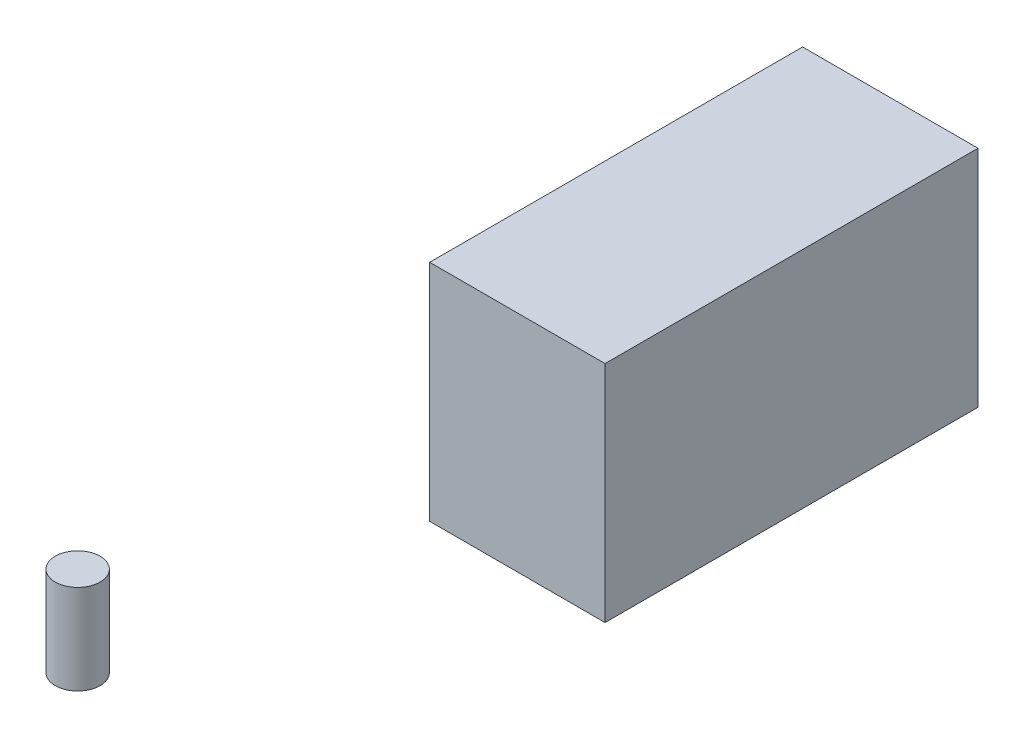
SolidWorks part; units mm, degrees
ref_plane "Alzado" through (0, 0, 0) normal (0, 0, 1) x (1, 0, 0)
ref_plane "Planta" through (0, 0, 0) normal (0, 1, 0) x (1, 0, 0)
ref_plane "Vista lateral" through (0, 0, 0) normal (1, 0, 0) x (0, 0, -1)
sketch "Croquis1" plane through (0, 0, 0) normal (0, 1, 0) x (1, 0, 0)
  circle A0 centre (0, 0) radius 2.5
  dimension "D1" = 5
extrude "Saliente-Extruir1" add sketch "Croquis1" along normal blind 10
sketch "Croquis2" plane through (0, 0, 0) normal (0, 1, 0) x (1, 0, 0)
  line L0 (0, 0) -> (5, 0) construction
  line L1 (5, 0) -> (5, 75.7822) construction
  line L3 (5, 75.7822) -> (24.5472, 75.7822)
  line L4 (5, 75.7822) -> (5, 34.2232)
  line L5 (5, 34.2232) -> (24.5472, 34.2232)
  line L6 (24.5472, 75.7822) -> (24.5472, 34.2232)
  dimension "D1" = 5
extrude "Saliente-Extruir2" add sketch "Croquis2" along normal blind 25 separate body
